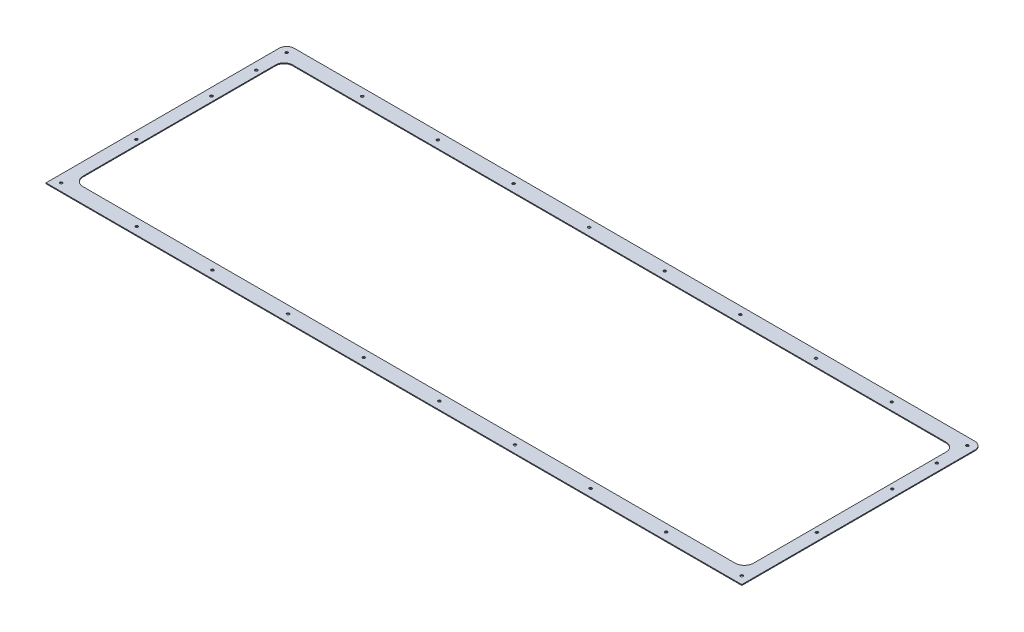
SolidWorks part; units mm, degrees
ref_plane "Płaszczyzna przednia" through (0, 0, 0) normal (0, 0, 1) x (1, 0, 0)
ref_plane "Płaszczyzna górna" through (0, 0, 0) normal (0, 1, 0) x (1, 0, 0)
ref_plane "Płaszczyzna prawa" through (0, 0, 0) normal (1, 0, 0) x (0, 0, -1)
sketch "Szkic4" plane through (0, 1505.9474, 0) normal (0, 1, 0) x (1, 0, 0)
  line L4 (12185.9797, -423.3745) -> (11379.9797, -423.3745) construction
  line L12 (11370.9797, -709.3745) -> (12194.9797, -709.3745)
  line L13 (12194.9797, -709.3745) -> (12194.9797, -433.3745)
  line L14 (12185.9797, -424.3745) -> (11379.9797, -424.3745)
  line L15 (11370.9797, -433.3745) -> (11370.9797, -709.3745)
  line L16 (11385.9797, -452.3745) -> (11385.9797, -680.3745)
  line L17 (11396.9797, -691.3745) -> (12168.9797, -691.3745)
  line L18 (12179.9797, -680.3745) -> (12179.9797, -452.3745)
  line L19 (12169.9797, -442.3745) -> (11395.9797, -442.3745)
  circle A1 centre (11379.9797, -433.3745) radius 1.55 construction
  arc A2 (12169.9797, -442.3745) -> (12179.9797, -452.3745) centre (12169.9797, -452.3745) cw
  arc A3 (11395.9797, -442.3745) -> (11385.9797, -452.3745) centre (11395.9797, -452.3745) ccw
  circle A6 centre (11469.5397, -433.3745) radius 1.55 construction
  circle A7 centre (11559.0947, -433.3745) radius 1.55 construction
  circle A8 centre (11648.6497, -433.3745) radius 1.55 construction
  circle A9 centre (11738.2047, -433.3745) radius 1.55 construction
  circle A10 centre (11827.7597, -433.3745) radius 1.55 construction
  circle A11 centre (11917.3147, -433.3745) radius 1.55 construction
  circle A12 centre (12006.8697, -433.3745) radius 1.55 construction
  circle A13 centre (12096.4247, -433.3745) radius 1.55 construction
  circle A14 centre (12185.9797, -433.3745) radius 1.55 construction
  circle A16 centre (12185.9797, -469.3745) radius 1.55 construction
  circle A17 centre (12185.9797, -522.3745) radius 1.55 construction
  circle A18 centre (12185.9797, -611.3745) radius 1.55 construction
  circle A19 centre (12185.9797, -700.3745) radius 1.55 construction
  circle A21 centre (12096.4197, -700.3745) radius 1.55 construction
  circle A22 centre (12006.8647, -700.3745) radius 1.55 construction
  circle A23 centre (11917.3097, -700.3745) radius 1.55 construction
  circle A24 centre (11827.7547, -700.3745) radius 1.55 construction
  circle A25 centre (11738.1997, -700.3745) radius 1.55 construction
  circle A26 centre (11648.6447, -700.3745) radius 1.55 construction
  circle A27 centre (11559.0897, -700.3745) radius 1.55 construction
  circle A28 centre (11469.5347, -700.3745) radius 1.55 construction
  circle A29 centre (11379.9797, -700.3745) radius 1.55 construction
  circle A31 centre (11379.9797, -611.3745) radius 1.55 construction
  circle A32 centre (11379.9797, -522.3745) radius 1.55 construction
  circle A33 centre (11379.9797, -469.3745) radius 1.55 construction
  circle A35 centre (11379.9797, -433.3745) radius 1.55
  circle A36 centre (11469.5397, -433.3745) radius 1.55
  circle A37 centre (11559.0947, -433.3745) radius 1.55
  circle A38 centre (11648.6497, -433.3745) radius 1.55
  circle A39 centre (11738.2047, -433.3745) radius 1.55
  circle A40 centre (11827.7597, -433.3745) radius 1.55
  circle A41 centre (11917.3147, -433.3745) radius 1.55
  circle A42 centre (12006.8697, -433.3745) radius 1.55
  circle A43 centre (12096.4247, -433.3745) radius 1.55
  circle A44 centre (12185.9797, -433.3745) radius 1.55
  arc A45 (12194.9797, -433.3745) -> (12185.9797, -424.3745) centre (12185.9797, -433.3745) ccw
  circle A46 centre (12185.9797, -469.3745) radius 1.55
  circle A47 centre (12185.9797, -522.3745) radius 1.55
  circle A48 centre (12185.9797, -611.3745) radius 1.55
  circle A49 centre (12185.9797, -700.3745) radius 1.55
  arc A50 (11379.9797, -424.3745) -> (11370.9797, -433.3745) centre (11379.9797, -433.3745) ccw
  circle A51 centre (12096.4197, -700.3745) radius 1.55
  circle A52 centre (12006.8647, -700.3745) radius 1.55
  circle A53 centre (11917.3097, -700.3745) radius 1.55
  circle A54 centre (11827.7547, -700.3745) radius 1.55
  circle A55 centre (11738.1997, -700.3745) radius 1.55
  circle A56 centre (11648.6447, -700.3745) radius 1.55
  circle A57 centre (11559.0897, -700.3745) radius 1.55
  circle A58 centre (11469.5347, -700.3745) radius 1.55
  circle A59 centre (11379.9797, -700.3745) radius 1.55
  circle A61 centre (11379.9797, -611.3745) radius 1.55
  circle A62 centre (11379.9797, -522.3745) radius 1.55
  circle A63 centre (11379.9797, -469.3745) radius 1.55
  arc A64 (11385.9797, -680.3745) -> (11396.9797, -691.3745) centre (11396.9797, -680.3745) ccw
  arc A65 (12168.9797, -691.3745) -> (12179.9797, -680.3745) centre (12168.9797, -680.3745) ccw
  dimension "D5" = 10
  dimension "D1" = 18
  dimension "D2" = 249
  dimension "D3" = 18
  dimension "D4" = 1
extrude "Dodanie-wyciągnięcie1" add sketch "Szkic4" along normal blind 1
